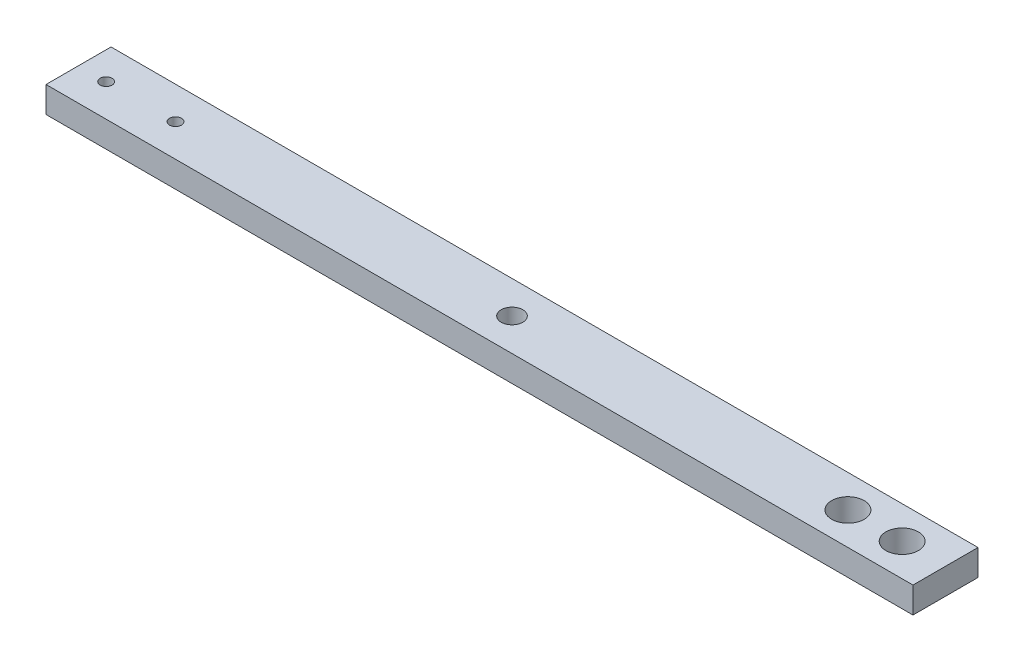
SolidWorks part; units mm, degrees
ref_plane "Front Plane" through (0, 0, 0) normal (0, 0, 1) x (1, 0, 0)
ref_plane "Top Plane" through (0, 0, 0) normal (0, 1, 0) x (1, 0, 0)
ref_plane "Right Plane" through (0, 0, 0) normal (1, 0, 0) x (0, 0, -1)
sketch "Sketch1" plane through (0, 0, 0) normal (0, 1, 0) x (1, 0, 0)
  line L0 (-200, 0) -> (-187.25, 0) construction
  line L1 (-200, -15) -> (200, -15)
  line L2 (-200, -15) -> (-200, 15)
  line L3 (-200, 15) -> (200, 15)
  line L4 (200, -15) -> (200, 15)
  line L5 (-200, -15) -> (200, 15) construction
  line L6 (-200, 15) -> (200, -15) construction
  line L7 (-187.25, 0) -> (-155.25, 0) construction
  circle A0 centre (0, 0) radius 5
  circle A1 centre (-187.25, 0) radius 2.75
  circle A2 centre (-155.25, 0) radius 2.75
  point P0 (0, 0)
  dimension "D3" = 12.75
  dimension "D4" = 32
  dimension "D1" = 30
  dimension "D2" = 400
extrude "Boss-Extrude1" add sketch "Sketch1" along normal blind 12
sketch "Sketch2" plane through (0, 0, 0) normal (0, 1, 0) x (1, 0, 0)
  line L0 (0, 0) -> (200, 0) construction
  line L1 (200, -15) -> (200, 15) construction
  line L2 (200, 0) -> (180, 0) construction
  line L3 (180, 0) -> (155, 0) construction
  circle A0 centre (155, 0) radius 7.5
  circle A1 centre (180, 0) radius 7.5
  dimension "D3" = 15
  dimension "D4" = 15
  dimension "D1" = 20
  dimension "D2" = 25
extrude "Cut-Extrude1" cut sketch "Sketch2" along normal blind 20
